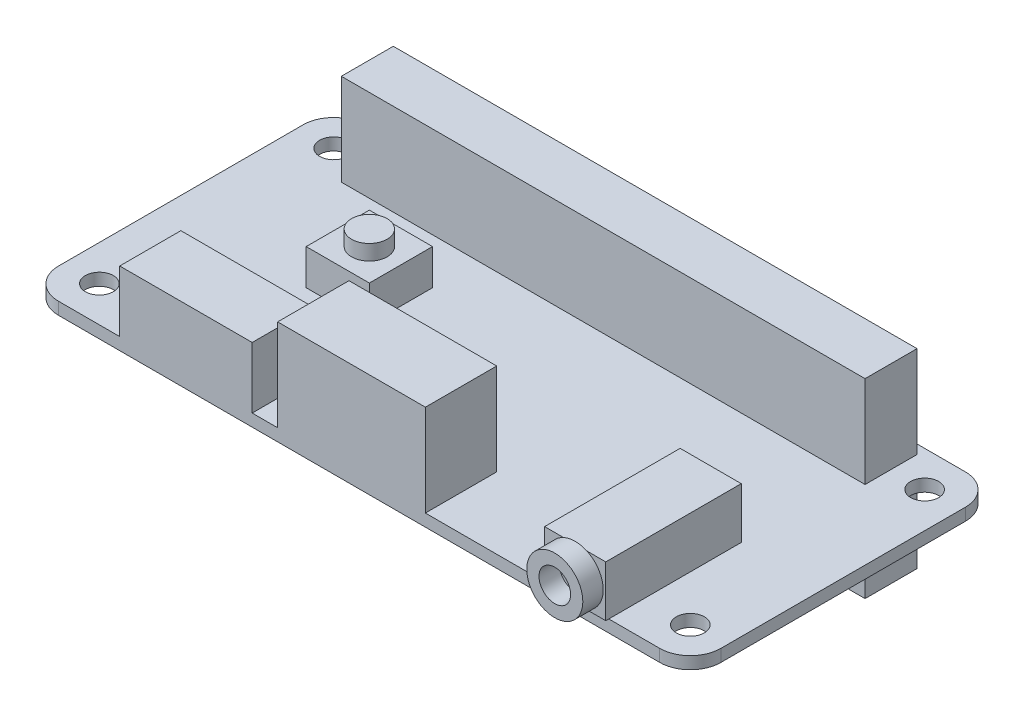
SolidWorks part; units mm, degrees
ref_plane "前视基准面" through (0, 0, 0) normal (0, 0, 1) x (1, 0, 0)
ref_plane "上视基准面" through (0, 0, 0) normal (0, 1, 0) x (1, 0, 0)
ref_plane "右视基准面" through (0, 0, 0) normal (1, 0, 0) x (0, 0, -1)
sketch "草图1" plane through (0, 0, 0) normal (0, 1, 0) x (1, 0, 0)
  line L1 (-29.5, 15) -> (29.5, 15)
  line L2 (-32.5, 12) -> (-32.5, -12)
  line L3 (-29.5, -15) -> (29.5, -15)
  line L4 (32.5, 12) -> (32.5, -12)
  line L5 (-32.5, 15) -> (32.5, -15) construction
  line L6 (-32.5, -15) -> (32.5, 15) construction
  arc A0 (29.5, 15) -> (32.5, 12) centre (29.5, 12) cw
  arc A1 (29.5, -15) -> (32.5, -12) centre (29.5, -12) ccw
  arc A2 (-32.5, -12) -> (-29.5, -15) centre (-29.5, -12) ccw
  arc A3 (-29.5, 15) -> (-32.5, 12) centre (-29.5, 12) ccw
  point P0 (0, 0)
  dimension "D3" = 3
  dimension "D1" = 65
  dimension "D2" = 30
extrude "凸台-拉伸1" add sketch "草图1" along normal blind 1.2
sketch "草图2" plane through (0, 1.2, 0) normal (0, 1, 0) x (1, 0, 0)
  line L0 (-29.5, -15) -> (29.5, -15) construction
  line L1 (32.5, -12) -> (32.5, 12) construction
  line L2 (29.5, 15) -> (-29.5, 15) construction
  circle A0 centre (29, -11.5) radius 1.375
  circle A1 centre (29, 11.5) radius 1.375
  circle A2 centre (-29, -11.5) radius 1.375
  circle A3 centre (-29, 11.5) radius 1.375
  dimension "D1" = 2.75
  dimension "D2" = 3.5
  dimension "D3" = 3.5
  dimension "D4" = 3.5
  dimension "D5" = 3.5
extrude "切除-拉伸1" cut sketch "草图2" against normal blind 1.2
sketch "草图3" plane through (0, 1.2, 0) normal (0, 1, 0) x (1, 0, 0)
  line L0 (-29.5, -15) -> (29.5, -15) construction
  line L1 (24.5, -15) -> (18.5, -15)
  line L2 (24.5, -15) -> (24.5, -2)
  line L3 (24.5, -2) -> (18.5, -2)
  line L4 (18.5, -15) -> (18.5, -2)
  line L5 (32.5, -12) -> (32.5, 12) construction
  dimension "D1" = 13
  dimension "D2" = 6
  dimension "D3" = 8
extrude "凸台-拉伸2" add sketch "草图3" along normal blind 5
sketch "草图4" plane through (0, 0, 15) normal (0, 0, 1) x (1, 0, 0)
  line L1 (18.5, 1.2) -> (24.5, 1.2)
  line L2 (18.5, 1.2) -> (18.5, 6.2)
  line L3 (18.5, 6.2) -> (24.5, 6.2)
  line L4 (24.5, 1.2) -> (24.5, 6.2)
extrude "凸台-拉伸3" add sketch "草图4" along normal blind 0.3
sketch "草图5" plane through (0, 1.2, 0) normal (0, 1, 0) x (1, 0, 0)
  line L0 (32.5, -12) -> (32.5, 12) construction
  line L1 (6.5, -8) -> (-8, -8)
  line L2 (6.5, -8) -> (6.5, -15)
  line L3 (6.5, -15) -> (-8, -15)
  line L4 (-8, -8) -> (-8, -15)
  line L5 (-29.5, -15) -> (18.5, -15) construction
  dimension "D1" = 26
  dimension "D2" = 7
  dimension "D3" = 14.5
extrude "凸台-拉伸4" add sketch "草图5" along normal blind 9
sketch "草图6" plane through (0, 1.2, 0) normal (0, 1, 0) x (1, 0, 0)
  line L0 (-29.5, -15) -> (-8, -15) construction
  line L1 (-10.5, -15) -> (-23.5, -15)
  line L2 (-10.5, -15) -> (-10.5, -9)
  line L3 (-10.5, -9) -> (-23.5, -9)
  line L4 (-23.5, -15) -> (-23.5, -9)
  dimension "D1" = 6
  dimension "D2" = 13
  dimension "D3" = 2.5
extrude "凸台-拉伸5" add sketch "草图6" along normal blind 6
sketch "草图11" plane through (0, 0, 0) normal (0, -1, 0) x (1, 0, 0)
  line L0 (29.5, -15) -> (-29.5, -15) construction
  line L1 (25.65, -14.1) -> (-25.75, -14.1)
  line L2 (25.65, -14.1) -> (25.65, -9)
  line L3 (25.65, -9) -> (-25.75, -9)
  line L4 (-25.75, -14.1) -> (-25.75, -9)
  line L5 (32.5, 12) -> (32.5, -12) construction
  dimension "D1" = 51.4
  dimension "D2" = 5.1
  dimension "D3" = 0.9
  dimension "D4" = 6.85
extrude "凸台-拉伸9" add sketch "草图11" along normal blind 8.5
sketch "草图12" plane through (0, 1.2, 0) normal (0, 1, 0) x (1, 0, 0)
  line L0 (-32.5, 12) -> (-32.5, -12) construction
  line L1 (-12.3, -1.7) -> (-18.5, -1.7)
  line L2 (-12.3, -1.7) -> (-12.3, 4.5)
  line L3 (-12.3, 4.5) -> (-18.5, 4.5)
  line L4 (-18.5, -1.7) -> (-18.5, 4.5)
  line L5 (29.5, 15) -> (-29.5, 15) construction
  dimension "D1" = 6.2
  dimension "D2" = 6.2
  dimension "D3" = 14
  dimension "D4" = 10.5
extrude "凸台-拉伸10" add sketch "草图12" along normal blind 3.5
sketch "草图13" plane through (0, 4.7, 0) normal (0, 1, 0) x (1, 0, 0)
  line L0 (-18.5, -1.7) -> (-12.3, -1.7) construction
  line L1 (-18.5, 4.5) -> (-18.5, -1.7) construction
  circle A0 centre (-15.4, 1.4) radius 1.75
  point P2 (0, 0)
  point P5 (-15.4, -1.7)
  point P8 (0, 0)
  point P9 (-18.5, 1.4)
  dimension "D1" = 3.5
extrude "凸台-拉伸11" add sketch "草图13" along normal blind 1.5
sketch "草图15" plane through (0, 0, 15.3) normal (0, 0, 1) x (1, 0, 0)
  line L0 (24.5, 6.2) -> (18.5, 6.2) construction
  circle A0 centre (21.5, 3.7) radius 1.55
  circle A1 centre (21.5, 3.7) radius 2.75
  point P3 (0, 0)
  point P6 (21.5, 6.2)
extrude "凸台-拉伸13" add sketch "草图15" along normal blind 2
sketch "草图16" plane through (0, 1.2, 0) normal (0, 1, 0) x (1, 0, 0)
  line L4 (25.65, 9) -> (25.65, 14.1)
  line L5 (-25.75, 9) -> (25.65, 9)
  line L6 (-25.75, 14.1) -> (-25.75, 9)
  line L7 (25.65, 14.1) -> (-25.75, 14.1)
  line L8 (25.65, 9) -> (25.65, 14.1)
  line L9 (-25.75, 9) -> (25.65, 9)
  line L10 (-25.75, 14.1) -> (-25.75, 9)
  line L11 (25.65, 14.1) -> (-25.75, 14.1)
  dimension "D1" = 0
extrude "凸台-拉伸14" add sketch "草图16" along normal blind 9
